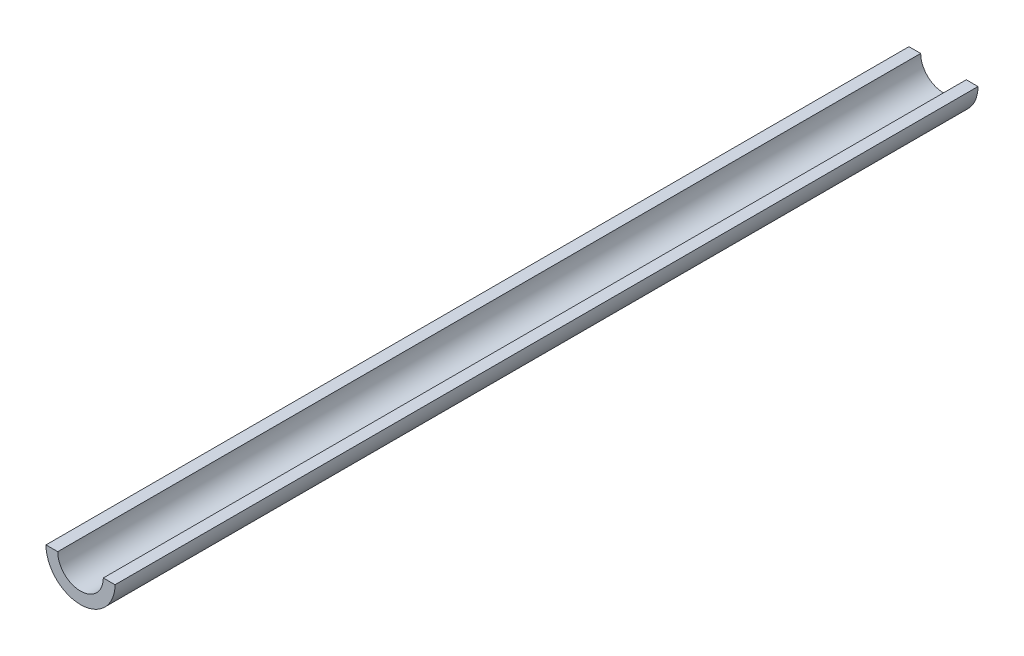
SolidWorks part; units mm, degrees
ref_plane "前视基准面" through (0, 0, 0) normal (0, 0, 1) x (1, 0, 0)
ref_plane "上视基准面" through (0, 0, 0) normal (0, 1, 0) x (1, 0, 0)
ref_plane "右视基准面" through (0, 0, 0) normal (1, 0, 0) x (0, 0, -1)
sketch "草图1" plane through (0, 0, 0) normal (0, 0, 1) x (1, 0, 0)
  line L0 (-10, 0) -> (-6.6, 0)
  line L1 (6.6, 0) -> (10, 0)
  arc A0 (-10, 0) -> (10, 0) centre (0, 0) ccw
  arc A1 (-6.6, 0) -> (6.6, 0) centre (0, 0) ccw
  dimension "D1" = 3.4
  dimension "D2" = 20
extrude "凸台-拉伸1" add sketch "草图1" along normal blind 250
